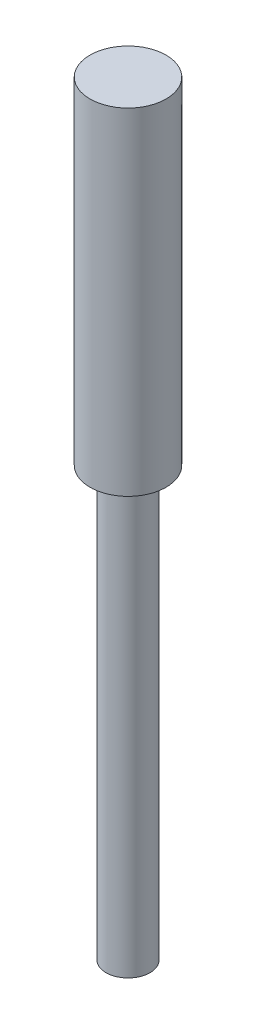
SolidWorks part; units mm, degrees
ref_plane "Front Plane" through (0, 0, 0) normal (0, 0, 1) x (1, 0, 0)
ref_plane "Top Plane" through (0, 0, 0) normal (0, 1, 0) x (1, 0, 0)
ref_plane "Right Plane" through (0, 0, 0) normal (1, 0, 0) x (0, 0, -1)
sketch "Sketch1" plane through (0, 0, 0) normal (0, 0, 1) x (1, 0, 0)
  line L0 (0, 0) -> (0, 42.9111) construction
  line L1 (0, 0) -> (1.375, 0)
  line L2 (1.375, 0) -> (1.375, 26.75)
  line L3 (1.375, 26.75) -> (2.375, 26.75)
  line L4 (2.375, 26.75) -> (2.375, 47.75)
  line L5 (2.375, 47.75) -> (0, 47.75)
  line L6 (0, 47.75) -> (0, 0)
  point P7 (0, 42.9111)
  point P9 (0, 0)
  dimension "D1" = 2.75
  dimension "D2" = 26.75
  dimension "D3" = 4.75
  dimension "D4" = 21
revolve "Revolve1" add sketch "Sketch1" angle 360 about L0
